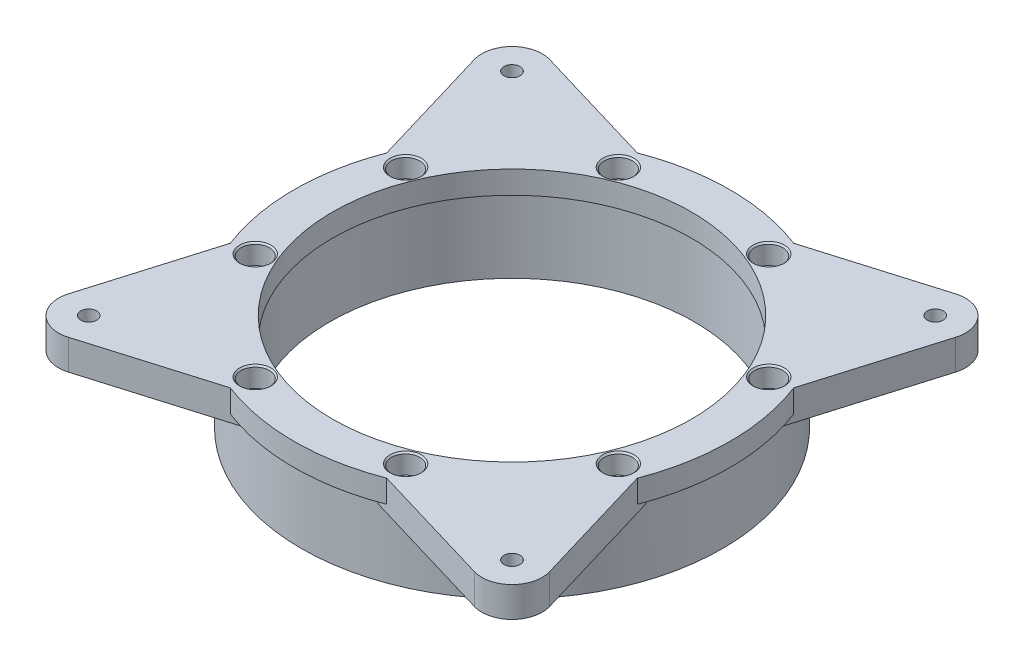
SolidWorks part; units mm, degrees
ref_plane "Front Plane" through (0, 0, 0) normal (0, 0, 1) x (1, 0, 0)
ref_plane "Top Plane" through (0, 0, 0) normal (0, 1, 0) x (1, 0, 0)
ref_plane "Right Plane" through (0, 0, 0) normal (1, 0, 0) x (0, 0, -1)
sketch "Sketch1" plane through (0, 0, 0) normal (0, 1, 0) x (1, 0, 0)
  circle A0 centre (112.8644, 65.4004) radius 88.395
  circle A2 centre (112.8644, 65.4004) radius 76.1365
  circle A3 centre (81.2739, 141.6667) radius 3.556
  circle A4 centre (144.4549, 141.6667) radius 3.556
  circle A5 centre (36.5981, 96.991) radius 3.556
  circle A6 centre (36.5981, 33.8099) radius 3.556
  circle A7 centre (81.2739, -10.8658) radius 3.556
  circle A8 centre (144.4549, -10.8658) radius 3.7114
  circle A9 centre (189.1306, 33.8099) radius 3.556
  circle A10 centre (189.1306, 96.991) radius 3.556
sketch "Sketch2" plane through (0, 0, 0) normal (0, 1, 0) x (1, 0, 0)
  circle A0 centre (112.8644, 65.4004) radius 88.395
  circle A4 centre (112.8644, 65.4004) radius 76.6365
  circle A5 centre (112.8644, 65.4004) radius 76.6365
  dimension "D2" = 176.79
  dimension "D1" = 0.5
extrude "Boss-Extrude1" add sketch "Sketch2" along normal blind 40.64
sketch "Sketch7" plane through (0, 40.64, 0) normal (0, 1, 0) x (1, 0, 0)
  line L0 (5.1013, 173.1635) -> (112.8644, 65.4004) construction
  line L1 (27.5864, 166.473) -> (85.16, 149.3418)
  line L2 (11.7918, 150.6785) -> (28.9231, 93.1048)
  line L3 (198.1424, 166.473) -> (140.5688, 149.3418)
  line L4 (213.9369, 150.6785) -> (196.8057, 93.1048)
  line L5 (213.9369, -19.8776) -> (196.8057, 37.696)
  line L6 (198.1424, -35.6721) -> (140.5688, -18.5409)
  line L7 (27.5864, -35.6721) -> (85.16, -18.5409)
  line L8 (11.7918, -19.8776) -> (28.9231, 37.696)
  arc A0 (85.16, 149.3418) -> (28.9231, 93.1048) centre (112.8644, 65.4004) ccw
  arc A1 (27.5864, 166.473) -> (11.7918, 150.6785) centre (23.9644, 154.3004) ccw
  circle A2 centre (112.8644, 65.4004) radius 88.395 construction
  arc A3 (196.8057, 93.1048) -> (140.5688, 149.3418) centre (112.8644, 65.4004) ccw
  arc A4 (213.9369, 150.6785) -> (198.1424, 166.473) centre (201.7644, 154.3004) ccw
  arc A5 (140.5688, -18.5409) -> (196.8057, 37.696) centre (112.8644, 65.4004) ccw
  arc A6 (198.1424, -35.6721) -> (213.9369, -19.8776) centre (201.7644, -23.4996) ccw
  arc A7 (28.9231, 37.696) -> (85.16, -18.5409) centre (112.8644, 65.4004) ccw
  arc A8 (11.7918, -19.8776) -> (27.5864, -35.6721) centre (23.9644, -23.4996) ccw
  point P28 (112.8644, 65.4004)
  dimension "D3" = 25.4
  dimension "D5" = 4
  dimension "D1" = 88.9
  dimension "D2" = 88.9
  dimension "D4" = 152.4
extrude "Boss-Extrude2" add sketch "Sketch7" against normal blind 12.7
sketch "Sketch8" plane through (0, 27.94, 0) normal (0, -1, 0) x (1, 0, 0)
  circle A0 centre (23.9644, 23.4996) radius 7.1842
  circle A1 centre (201.7644, 23.4996) radius 7.1842
  circle A2 centre (201.7644, -154.3004) radius 7.1842
  circle A3 centre (23.9644, -154.3004) radius 7.1842
  point P0 (23.9644, 23.4996)
  point P5 (201.7644, 23.4996)
  point P7 (201.7644, -154.3004)
  point P9 (23.9644, -154.3004)
  dimension "D1" = 2
  dimension "D2" = 2
hole_wizard "CBORE for 1/4 Socket Head Cap Screw1" positions "Sketch8" profile "Sketch9" counterbore size "1/4" standard "ANSI Inch" end condition through all
sketch "Sketch9" plane through (23.9644, 27.94, 23.4996) normal (1, 0, 0) x (0, 0, -1)
  line L0 (0, 0) -> (0, 12.7)
  line L1 (0, 12.7) -> (3.3782, 12.7)
  line L3 (3.3782, 12.7) -> (3.3782, 6.35)
  line L4 (5.5562, 6.35) -> (3.3782, 6.35)
  line L5 (5.5562, 6.35) -> (5.5562, 0.635)
  line L6 (5.5562, 0.635) -> (6.1913, 0)
  line L7 (6.1913, 0) -> (0, 0)
  line L8 (-5.5562, 0.635) -> (-6.1913, 0) construction
  line L11 (0, -6.35) -> (0, 107.95) construction
  dimension "Thru Hole Dia." = 6.7564
  dimension "Thru Hole Depth" = 12.7
  dimension "C'Bore Dia." = 11.1125
  dimension "C'Bore Depth" = 6.35
  dimension "Near C'Sink Dia." = 12.3825
  dimension "Near C'Sink Angle" = 90
sketch "Sketch10" plane through (0, 40.64, 0) normal (0, 1, 0) x (1, 0, 0)
  circle A2 centre (112.8644, 65.4004) radius 75.3865
  circle A3 centre (112.8644, 65.4004) radius 75.3865
  circle A6 centre (112.8644, 65.4004) radius 91.57
  circle A7 centre (112.8644, 65.4004) radius 91.57
  dimension "D1" = 1.25
  dimension "D2" = 3.175
extrude "Boss-Extrude3" add sketch "Sketch10" against normal blind 9.525
sketch "Sketch5" [suppressed] plane through (0, 38.1, 0) normal (0, 1, 0) x (1, 0, 0)
  circle A12 centre (36.5981, 96.991) radius 5.056
  circle A13 centre (36.5981, 96.991) radius 5.056
  circle A15 centre (81.2739, 141.6667) radius 5.056
  circle A16 centre (81.2739, 141.6667) radius 5.056
  circle A18 centre (144.4549, 141.6667) radius 5.056
  circle A19 centre (144.4549, 141.6667) radius 5.056
  circle A21 centre (189.1306, 96.991) radius 5.056
  circle A22 centre (189.1306, 96.991) radius 5.056
  circle A24 centre (36.5981, 33.8099) radius 5.056
  circle A25 centre (36.5981, 33.8099) radius 5.056
  circle A27 centre (81.2739, -10.8658) radius 5.056
  circle A28 centre (81.2739, -10.8658) radius 5.056
  circle A30 centre (144.4549, -10.8658) radius 5.2114
  circle A31 centre (144.4549, -10.8658) radius 5.2114
  circle A33 centre (189.1306, 33.8099) radius 5.056
  circle A34 centre (189.1306, 33.8099) radius 5.056
  dimension "D1" = 1.5
  dimension "D2" = 1.5
  dimension "D3" = 1.5
  dimension "D4" = 1.5
  dimension "D5" = 1.5
  dimension "D6" = 1.5
  dimension "D7" = 1.5
  dimension "D8" = 1.5
sketch "Sketch11" plane through (0, 40.64, 0) normal (0, 1, 0) x (1, 0, 0)
  point P0 (36.5981, 33.8099)
  point P3 (36.5981, 96.991)
  point P6 (81.2739, 141.6667)
  point P9 (144.4549, 141.6667)
  point P12 (189.1306, 96.991)
  point P15 (189.1306, 33.8099)
  point P18 (144.4549, -10.8658)
  point P21 (81.2739, -10.8658)
hole_wizard "CBORE for 1/4 Button Head Cap Screw1" positions "Sketch11" profile "Sketch12" counterbore size "1/4" standard "ANSI Inch" end condition through all
sketch "Sketch12" plane through (36.5981, 40.64, -33.8099) normal (1, 0, 0) x (0, 0, 1)
  line L0 (0, 0) -> (0, 40.64)
  line L1 (0, 40.64) -> (3.3782, 40.64)
  line L3 (3.3782, 40.64) -> (3.3782, 8.3528)
  line L4 (5.9538, 8.3528) -> (3.3782, 8.3528)
  line L5 (5.9538, 8.3528) -> (5.9538, 0.635)
  line L6 (5.9538, 0.635) -> (6.5888, 0)
  line L7 (6.5888, 0) -> (0, 0)
  line L8 (-5.9538, 0.635) -> (-6.5888, 0) construction
  line L11 (0, -6.35) -> (0, 107.95) construction
  dimension "Thru Hole Dia." = 6.7564
  dimension "Thru Hole Depth" = 40.64
  dimension "C'Bore Dia." = 11.9075
  dimension "C'Bore Depth" = 8.3528
  dimension "Near C'Sink Dia." = 13.1775
  dimension "Near C'Sink Angle" = 90
